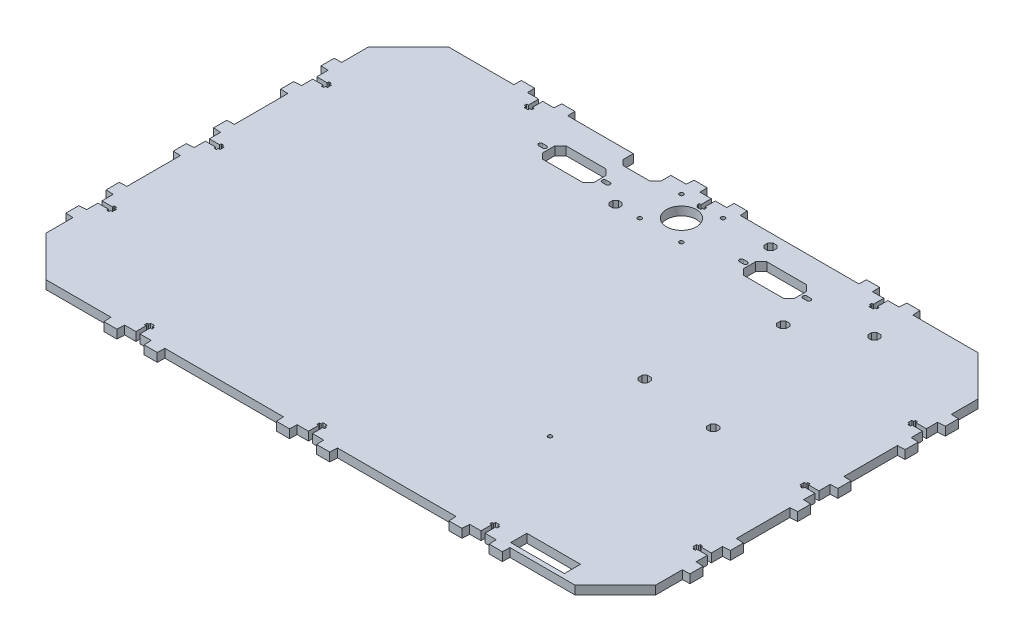
SolidWorks part; units mm, degrees
ref_plane "Front Plane" through (0, 0, 0) normal (0, 0, 1) x (1, 0, 0)
ref_plane "Top Plane" through (0, 0, 0) normal (0, 1, 0) x (1, 0, 0)
ref_plane "Right Plane" through (0, 0, 0) normal (1, 0, 0) x (0, 0, -1)
sketch "Sketch1" plane through (0, 0, 0) normal (0, 1, 0) x (1, 0, 0)
  line L0 (-96.3061, 126.6946) -> (-92.1061, 130.8946)
  line L1 (-92.1061, 130.8946) -> (-62.3561, 130.8946)
  line L2 (-62.3561, 130.8946) -> (-58.1561, 126.6946)
  line L3 (-58.1561, 126.6946) -> (-58.1561, 117.7078)
  line L4 (-58.1561, 117.7078) -> (-62.3561, 113.5078)
  line L5 (-62.3561, 113.5078) -> (-92.1061, 113.5078)
  line L6 (-92.1061, 113.5078) -> (-96.3061, 117.7078)
  line L7 (-96.3061, 117.7078) -> (-96.3061, 126.6946)
  line L8 (-52.1061, 120.7012) -> (-55.1061, 120.7012)
  line L9 (-52.1061, 123.7012) -> (-55.1061, 123.7012)
  line L10 (-102.3561, 123.7012) -> (-99.3561, 123.7012)
  line L11 (-102.3561, 120.7012) -> (-99.3561, 120.7012)
  line L12 (146.0113, 0.3464) -> (148.0322, 2.3673)
  line L13 (143.1576, -145.6002) -> (143.1576, -133.6002)
  line L14 (143.1576, -145.6002) -> (183.1576, -145.6002)
  line L15 (143.1576, -133.6002) -> (183.1576, -133.6002)
  line L16 (188.5789, -149.1002) -> (194.5451, -149.1002)
  line L17 (194.5451, -149.1002) -> (224.5789, -119.0664)
  line L18 (224.5789, -119.0664) -> (224.5789, -99.2238)
  line L19 (224.5789, -99.2238) -> (230.0789, -98.9488)
  line L20 (230.0789, -98.9488) -> (230.0789, -89.2488)
  line L21 (230.0789, -89.2488) -> (224.5789, -88.9738)
  line L22 (224.5789, -88.9738) -> (224.5789, -80.6002)
  line L23 (224.5789, -80.6002) -> (216.8789, -80.6002)
  line L24 (216.8789, -80.6002) -> (216.8789, -81.8488)
  line L25 (216.8789, -81.8488) -> (215.0789, -81.8488)
  line L26 (215.0789, -81.8488) -> (215.0789, -80.6002)
  line L27 (215.0789, -80.6002) -> (213.6789, -80.6002)
  line L28 (213.6789, -80.6002) -> (213.6789, -77.5988)
  line L29 (213.6789, -77.5988) -> (215.0789, -77.5988)
  line L30 (215.0789, -77.5988) -> (215.0789, -76.3488)
  line L31 (215.0789, -76.3488) -> (216.8789, -76.3488)
  line L32 (216.8789, -76.3488) -> (216.8789, -77.5988)
  line L33 (216.8789, -77.5988) -> (224.5789, -77.5988)
  line L34 (224.5789, -77.5988) -> (224.5789, -69.2238)
  line L35 (224.5789, -69.2238) -> (230.0789, -68.9488)
  line L36 (230.0789, -68.9488) -> (230.0789, -59.2488)
  line L37 (230.0789, -59.2488) -> (224.5789, -58.9738)
  line L38 (224.5789, -58.9738) -> (224.5789, -19.1238)
  line L39 (224.5789, -19.1238) -> (230.0789, -18.8488)
  line L40 (230.0789, -18.8488) -> (230.0789, -9.1488)
  line L41 (230.0789, -9.1488) -> (224.5789, -8.8738)
  line L42 (224.5789, -8.8738) -> (224.5789, -0.5002)
  line L43 (224.5789, -0.5002) -> (216.8789, -0.5002)
  line L44 (216.8789, -0.5002) -> (216.8789, -1.7488)
  line L45 (216.8789, -1.7488) -> (215.0789, -1.7488)
  line L46 (215.0789, -1.7488) -> (215.0789, -0.5002)
  line L47 (215.0789, -0.5002) -> (213.6789, -0.5002)
  line L48 (213.6789, -0.5002) -> (213.6789, 2.5012)
  line L49 (213.6789, 2.5012) -> (215.0789, 2.5012)
  line L50 (215.0789, 2.5012) -> (215.0789, 3.7512)
  line L51 (215.0789, 3.7512) -> (216.8789, 3.7512)
  line L52 (216.8789, 3.7512) -> (216.8789, 2.5012)
  line L53 (216.8789, 2.5012) -> (224.5789, 2.5012)
  line L54 (224.5789, 2.5012) -> (224.5789, 10.8762)
  line L55 (224.5789, 10.8762) -> (230.0789, 11.1512)
  line L56 (230.0789, 11.1512) -> (230.0789, 20.8512)
  line L57 (230.0789, 20.8512) -> (224.5789, 21.1262)
  line L58 (224.5789, 21.1262) -> (224.5789, 60.9762)
  line L59 (224.5789, 60.9762) -> (230.0789, 61.2512)
  line L60 (230.0789, 61.2512) -> (230.0789, 70.9512)
  line L61 (230.0789, 70.9512) -> (224.5789, 71.2262)
  line L62 (224.5789, 71.2262) -> (224.5789, 79.5998)
  line L63 (224.5789, 79.5998) -> (216.8789, 79.5998)
  line L64 (216.8789, 79.5998) -> (216.8789, 78.3512)
  line L65 (216.8789, 78.3512) -> (215.0789, 78.3512)
  line L66 (215.0789, 78.3512) -> (215.0789, 79.5998)
  line L67 (215.0789, 79.5998) -> (213.6789, 79.5998)
  line L68 (213.6789, 79.5998) -> (213.6789, 82.6012)
  line L69 (213.6789, 82.6012) -> (215.0789, 82.6012)
  line L70 (215.0789, 82.6012) -> (215.0789, 83.8512)
  line L71 (215.0789, 83.8512) -> (216.8789, 83.8512)
  line L72 (216.8789, 83.8512) -> (216.8789, 82.6012)
  line L73 (216.8789, 82.6012) -> (224.5189, 82.6012)
  line L74 (224.5189, 82.6012) -> (224.5189, 90.9762)
  line L75 (224.5189, 90.9762) -> (230.0189, 91.2512)
  line L76 (230.0189, 91.2512) -> (230.0189, 100.9512)
  line L77 (230.0189, 100.9512) -> (224.5189, 101.2262)
  line L78 (224.5189, 101.2262) -> (224.5189, 121.0674)
  line L79 (224.5189, 121.0674) -> (194.6999, 150.8864)
  line L80 (194.6999, 150.8864) -> (188.5189, 150.8674)
  line L81 (188.5189, 150.8674) -> (146.1439, 150.9012)
  line L82 (146.1439, 150.9012) -> (145.8689, 156.4012)
  line L83 (145.8689, 156.4012) -> (136.1689, 156.4012)
  line L84 (136.1689, 156.4012) -> (135.8939, 150.9012)
  line L85 (135.8939, 150.9012) -> (127.5189, 150.9012)
  line L86 (127.5189, 150.9012) -> (127.5189, 143.2012)
  line L87 (127.5189, 143.2012) -> (128.7689, 143.2012)
  line L88 (128.7689, 143.2012) -> (128.7689, 141.4012)
  line L89 (128.7689, 141.4012) -> (127.5189, 141.4012)
  line L90 (127.5189, 141.4012) -> (127.5189, 140.0012)
  line L91 (127.5189, 140.0012) -> (124.5175, 140.0012)
  line L92 (124.5175, 140.0012) -> (124.5175, 141.4012)
  line L93 (124.5175, 141.4012) -> (123.2689, 141.4012)
  line L94 (123.2689, 141.4012) -> (123.2689, 143.2012)
  line L95 (123.2689, 143.2012) -> (124.5175, 143.2012)
  line L96 (124.5175, 143.2012) -> (124.5175, 150.9012)
  line L97 (124.5175, 150.9012) -> (116.1439, 150.9012)
  line L98 (116.1439, 150.9012) -> (115.8689, 156.4012)
  line L99 (115.8689, 156.4012) -> (106.1689, 156.4012)
  line L100 (106.1689, 156.4012) -> (105.8939, 150.9012)
  line L101 (105.8939, 150.9012) -> (17.6432, 150.9012)
  line L102 (17.6432, 150.9012) -> (17.3682, 156.4012)
  line L103 (17.3682, 156.4012) -> (7.6682, 156.4012)
  line L104 (7.6682, 156.4012) -> (7.3932, 150.9012)
  line L105 (7.3932, 150.9012) -> (-0.9804, 150.9012)
  line L106 (-0.9804, 150.9012) -> (-0.9804, 143.2012)
  line L107 (-0.9804, 143.2012) -> (0.2682, 143.2012)
  line L108 (0.2682, 143.2012) -> (0.2682, 141.4012)
  line L109 (0.2682, 141.4012) -> (-0.9804, 141.4012)
  line L110 (-0.9804, 141.4012) -> (-0.9804, 140.0012)
  line L111 (-0.9804, 140.0012) -> (-3.9818, 140.0012)
  line L112 (-3.9818, 140.0012) -> (-3.9818, 141.4012)
  line L113 (-3.9818, 141.4012) -> (-5.2318, 141.4012)
  line L114 (-5.2318, 141.4012) -> (-5.2318, 143.2012)
  line L115 (-5.2318, 143.2012) -> (-3.9818, 143.2012)
  line L116 (-3.9818, 143.2012) -> (-3.9818, 150.9012)
  line L117 (-3.9818, 150.9012) -> (-12.3568, 150.9012)
  line L118 (-12.3568, 150.9012) -> (-12.6318, 156.4012)
  line L119 (-12.6318, 156.4012) -> (-22.3318, 156.4012)
  line L120 (-22.3318, 156.4012) -> (-22.6068, 150.9012)
  line L121 (-22.6068, 150.9012) -> (-34.055, 150.9012)
  line L122 (-110.8561, 150.9012) -> (-111.1311, 156.4012)
  line L123 (-111.1311, 156.4012) -> (-120.8311, 156.4012)
  line L124 (-120.8311, 156.4012) -> (-121.1061, 150.9012)
  line L125 (-121.1061, 150.9012) -> (-129.4798, 150.9012)
  line L126 (-129.4798, 150.9012) -> (-129.4798, 143.2012)
  line L127 (-129.4798, 143.2012) -> (-128.2311, 143.2012)
  line L128 (-128.2311, 143.2012) -> (-128.2311, 141.4012)
  line L129 (-128.2311, 141.4012) -> (-129.4798, 141.4012)
  line L130 (-129.4798, 141.4012) -> (-129.4798, 140.0012)
  line L131 (-129.4798, 140.0012) -> (-132.4811, 140.0012)
  line L132 (-132.4811, 140.0012) -> (-132.4811, 141.4012)
  line L133 (-132.4811, 141.4012) -> (-133.7311, 141.4012)
  line L134 (-133.7311, 141.4012) -> (-133.7311, 143.2012)
  line L135 (-133.7311, 143.2012) -> (-132.4811, 143.2012)
  line L136 (-132.4811, 143.2012) -> (-132.4811, 150.9012)
  line L137 (-132.4811, 150.9012) -> (-140.8561, 150.9012)
  line L138 (-140.8561, 150.9012) -> (-141.1311, 156.4012)
  line L139 (-141.1311, 156.4012) -> (-150.8311, 156.4012)
  line L140 (-150.8311, 156.4012) -> (-151.1061, 150.9012)
  line L141 (-151.1061, 150.9012) -> (-199.6473, 150.9012)
  line L142 (-199.6473, 150.9012) -> (-229.4811, 121.0674)
  line L143 (-229.4811, 121.0674) -> (-229.4811, 101.2262)
  line L144 (-229.4811, 101.2262) -> (-234.9811, 100.9512)
  line L145 (-234.9811, 100.9512) -> (-234.9811, 91.2512)
  line L146 (-234.9811, 91.2512) -> (-229.4811, 90.9762)
  line L147 (-229.4811, 90.9762) -> (-229.4811, 82.6012)
  line L148 (-229.4811, 82.6012) -> (-221.7811, 82.6012)
  line L149 (-221.7811, 82.6012) -> (-221.7811, 83.8512)
  line L150 (-221.7811, 83.8512) -> (-219.9811, 83.8512)
  line L151 (-219.9811, 83.8512) -> (-219.9811, 82.6012)
  line L152 (-219.9811, 82.6012) -> (-218.5811, 82.6012)
  line L153 (-218.5811, 82.6012) -> (-218.5811, 79.5998)
  line L154 (-218.5811, 79.5998) -> (-219.9811, 79.5998)
  line L155 (-219.9811, 79.5998) -> (-219.9811, 78.3512)
  line L156 (-219.9811, 78.3512) -> (-221.7811, 78.3512)
  line L157 (-221.7811, 78.3512) -> (-221.7811, 79.5998)
  line L158 (-221.7811, 79.5998) -> (-229.4811, 79.5998)
  line L159 (-229.4811, 79.5998) -> (-229.4811, 71.2262)
  line L160 (-229.4811, 71.2262) -> (-234.9811, 70.9512)
  line L161 (-234.9811, 70.9512) -> (-234.9811, 61.2512)
  line L162 (-234.9811, 61.2512) -> (-229.4811, 60.9762)
  line L163 (-229.4811, 60.9762) -> (-229.4811, 21.2262)
  line L164 (-229.4811, 21.2262) -> (-234.9811, 20.9512)
  line L165 (-234.9811, 20.9512) -> (-234.9811, 11.2512)
  line L166 (-234.9811, 11.2512) -> (-229.4811, 10.9762)
  line L167 (-229.4811, 10.9762) -> (-229.4811, 2.6012)
  line L168 (-229.4811, 2.6012) -> (-221.7811, 2.6012)
  line L169 (-221.7811, 2.6012) -> (-221.7811, 3.8512)
  line L170 (-221.7811, 3.8512) -> (-219.9811, 3.8512)
  line L171 (-219.9811, 3.8512) -> (-219.9811, 2.6012)
  line L172 (-219.9811, 2.6012) -> (-218.5811, 2.6012)
  line L173 (-218.5811, 2.6012) -> (-218.5811, -0.4002)
  line L174 (-218.5811, -0.4002) -> (-219.9811, -0.4002)
  line L175 (-219.9811, -0.4002) -> (-219.9811, -1.6488)
  line L176 (-219.9811, -1.6488) -> (-221.7811, -1.6488)
  line L177 (-221.7811, -1.6488) -> (-221.7811, -0.4002)
  line L178 (-221.7811, -0.4002) -> (-229.4811, -0.4002)
  line L179 (-229.4811, -0.4002) -> (-229.4811, -8.7738)
  line L180 (-229.4811, -8.7738) -> (-234.9811, -9.0488)
  line L181 (-234.9811, -9.0488) -> (-234.9811, -18.7488)
  line L182 (-234.9811, -18.7488) -> (-229.4811, -19.0238)
  line L183 (-229.4811, -19.0238) -> (-229.4811, -58.7738)
  line L184 (-229.4811, -58.7738) -> (-234.9811, -59.0488)
  line L185 (-234.9811, -59.0488) -> (-234.9811, -68.7488)
  line L186 (-234.9811, -68.7488) -> (-229.4811, -69.0238)
  line L187 (-229.4811, -69.0238) -> (-229.4811, -77.3988)
  line L188 (-229.4811, -77.3988) -> (-221.7811, -77.3988)
  line L189 (-221.7811, -77.3988) -> (-221.7811, -76.1488)
  line L190 (-221.7811, -76.1488) -> (-219.9811, -76.1488)
  line L191 (-219.9811, -76.1488) -> (-219.9811, -77.3988)
  line L192 (-219.9811, -77.3988) -> (-218.5811, -77.3988)
  line L193 (-218.5811, -77.3988) -> (-218.5811, -80.4002)
  line L194 (-218.5811, -80.4002) -> (-219.9811, -80.4002)
  line L195 (-219.9811, -80.4002) -> (-219.9811, -81.6488)
  line L196 (-219.9811, -81.6488) -> (-221.7811, -81.6488)
  line L197 (-221.7811, -81.6488) -> (-221.7811, -80.4002)
  line L198 (-221.7811, -80.4002) -> (-229.4811, -80.4002)
  line L199 (-229.4811, -80.4002) -> (-229.4811, -88.7738)
  line L200 (-229.4811, -88.7738) -> (-234.9811, -89.0488)
  line L201 (-234.9811, -89.0488) -> (-234.9811, -98.7488)
  line L202 (-234.9811, -98.7488) -> (-229.4811, -99.0238)
  line L203 (-229.4811, -99.0238) -> (-229.4811, -119.0664)
  line L204 (-229.4811, -119.0664) -> (-199.4473, -149.1002)
  line L205 (-199.4473, -149.1002) -> (-151.1061, -149.1002)
  line L206 (-151.1061, -149.1002) -> (-150.8311, -154.6002)
  line L207 (-150.8311, -154.6002) -> (-141.1311, -154.6002)
  line L208 (-141.1311, -154.6002) -> (-140.8561, -149.1002)
  line L209 (-140.8561, -149.1002) -> (-132.4811, -149.1002)
  line L210 (-132.4811, -149.1002) -> (-132.4811, -141.4002)
  line L211 (-132.4811, -141.4002) -> (-133.7311, -141.4002)
  line L212 (-133.7311, -141.4002) -> (-133.7311, -139.6002)
  line L213 (-133.7311, -139.6002) -> (-132.4811, -139.6002)
  line L214 (-132.4811, -139.6002) -> (-132.4811, -138.2002)
  line L215 (-132.4811, -138.2002) -> (-129.4798, -138.2002)
  line L216 (-129.4798, -138.2002) -> (-129.4798, -139.6002)
  line L217 (-129.4798, -139.6002) -> (-128.2311, -139.6002)
  line L218 (-128.2311, -139.6002) -> (-128.2311, -141.4002)
  line L219 (-128.2311, -141.4002) -> (-129.4798, -141.4002)
  line L220 (-129.4798, -141.4002) -> (-129.4798, -149.1002)
  line L221 (-129.4798, -149.1002) -> (-121.1061, -149.1002)
  line L222 (-121.1061, -149.1002) -> (-120.8311, -154.6002)
  line L223 (-120.8311, -154.6002) -> (-111.1311, -154.6002)
  line L224 (-111.1311, -154.6002) -> (-110.8561, -149.1002)
  line L225 (-110.8561, -149.1002) -> (-22.6068, -149.1002)
  line L226 (-22.6068, -149.1002) -> (-22.3318, -154.6002)
  line L227 (-22.3318, -154.6002) -> (-12.6318, -154.6002)
  line L228 (-12.6318, -154.6002) -> (-12.3568, -149.1002)
  line L229 (-12.3568, -149.1002) -> (-3.9818, -149.1002)
  line L230 (-3.9818, -149.1002) -> (-3.9818, -141.4002)
  line L231 (-3.9818, -141.4002) -> (-5.2318, -141.4002)
  line L232 (-5.2318, -141.4002) -> (-5.2318, -139.6002)
  line L233 (-5.2318, -139.6002) -> (-3.9818, -139.6002)
  line L234 (-3.9818, -139.6002) -> (-3.9818, -138.2002)
  line L235 (-3.9818, -138.2002) -> (-0.9804, -138.2002)
  line L236 (-0.9804, -138.2002) -> (-0.9804, -139.6002)
  line L237 (-0.9804, -139.6002) -> (0.2682, -139.6002)
  line L238 (0.2682, -139.6002) -> (0.2682, -141.4002)
  line L239 (0.2682, -141.4002) -> (-0.9804, -141.4002)
  line L240 (-0.9804, -141.4002) -> (-0.9804, -149.1002)
  line L241 (-0.9804, -149.1002) -> (7.3932, -149.1002)
  line L242 (7.3932, -149.1002) -> (7.6682, -154.6002)
  line L243 (7.6682, -154.6002) -> (17.3682, -154.6002)
  line L244 (17.3682, -154.6002) -> (17.6432, -149.1002)
  line L245 (-34.626, 108.2512) -> (-32.605, 110.2722)
  line L246 (105.8939, -149.1002) -> (106.1689, -154.6002)
  line L247 (106.1689, -154.6002) -> (115.8689, -154.6002)
  line L248 (115.8689, -154.6002) -> (116.1439, -149.1002)
  line L249 (116.1439, -149.1002) -> (124.5175, -149.1002)
  line L250 (124.5175, -149.1002) -> (124.5175, -141.4002)
  line L251 (124.5175, -141.4002) -> (123.2689, -141.4002)
  line L252 (123.2689, -141.4002) -> (123.2689, -139.6002)
  line L253 (123.2689, -139.6002) -> (124.5175, -139.6002)
  line L254 (124.5175, -139.6002) -> (124.5175, -138.2002)
  line L255 (124.5175, -138.2002) -> (127.5189, -138.2002)
  line L256 (127.5189, -138.2002) -> (127.5189, -139.6002)
  line L257 (127.5189, -139.6002) -> (128.7689, -139.6002)
  line L258 (128.7689, -139.6002) -> (128.7689, -141.4002)
  line L259 (128.7689, -141.4002) -> (127.5189, -141.4002)
  line L260 (127.5189, -141.4002) -> (127.5189, -149.1002)
  line L261 (127.5189, -149.1002) -> (135.8939, -149.1002)
  line L262 (135.8939, -149.1002) -> (136.1689, -154.6002)
  line L263 (136.1689, -154.6002) -> (145.8689, -154.6002)
  line L264 (145.8689, -154.6002) -> (146.1439, -149.1002)
  line L265 (188.5789, -149.1002) -> (146.1439, -149.1002)
  line L266 (183.1576, -133.6002) -> (183.1576, -145.6002)
  line L267 (-39.505, 110.2722) -> (-37.484, 108.2512)
  line L268 (-37.484, 115.1512) -> (-39.505, 113.1302)
  line L269 (-34.626, 115.1512) -> (-37.484, 115.1512)
  line L270 (-37.484, 108.2512) -> (-34.626, 108.2512)
  line L271 (-39.505, 113.1302) -> (-39.505, 110.2722)
  line L272 (-32.605, 113.1302) -> (-34.626, 115.1512)
  line L273 (17.6432, -149.1002) -> (105.8939, -149.1002)
  line L274 (-2.4811, 140.0012) -> (-2.4811, 116.0719) construction
  line L275 (97.3939, 120.7012) -> (94.3939, 120.7012)
  line L276 (97.3939, 123.7012) -> (94.3939, 123.7012)
  line L277 (47.1439, 123.7012) -> (50.1439, 123.7012)
  line L278 (47.1439, 120.7012) -> (50.1439, 120.7012)
  line L279 (91.3439, 117.7078) -> (91.3439, 126.6946)
  line L280 (87.1439, 113.5078) -> (91.3439, 117.7078)
  line L281 (57.3939, 113.5078) -> (87.1439, 113.5078)
  line L282 (53.1939, 117.7078) -> (57.3939, 113.5078)
  line L283 (53.1939, 126.6946) -> (53.1939, 117.7078)
  line L284 (57.3939, 130.8946) -> (53.1939, 126.6946)
  line L285 (87.1439, 130.8946) -> (57.3939, 130.8946)
  line L286 (91.3439, 126.6946) -> (87.1439, 130.8946)
  line L287 (-77.2311, 113.5078) -> (-77.2311, 130.8946) construction
  line L288 (141.1322, 2.3673) -> (143.1532, 0.3464)
  line L289 (-32.605, 110.2722) -> (-32.605, 113.1302)
  line L290 (143.1532, 7.2464) -> (141.1322, 5.2254)
  line L291 (146.0113, 7.2464) -> (143.1532, 7.2464)
  line L292 (143.1532, 0.3464) -> (146.0113, 0.3464)
  line L293 (141.1322, 5.2254) -> (141.1322, 2.3673)
  line L294 (145.5822, 122.7964) -> (104.2222, 96.2964) construction
  line L295 (104.2222, 96.2964) -> (144.5822, 3.7964) construction
  line L296 (144.5822, 3.7964) -> (87.5822, 9.7964) construction
  line L297 (87.5822, 9.7964) -> (49.1672, 141.8464) construction
  line L298 (49.1672, 141.8464) -> (145.5822, 122.7964) construction
  line L299 (194.6999, 150.8864) -> (224.5189, 150.8864) construction
  line L300 (224.5189, 150.8864) -> (89.2289, -62.4036) construction
  line L301 (-62.055, 150.9012) -> (-110.8561, 150.9012)
  line L302 (-62.055, 150.9012) -> (-34.055, 150.9012) construction
  line L303 (-34.055, 150.9012) -> (-34.055, 143.4012)
  line L304 (-38.055, 139.4012) -> (-58.055, 139.4012)
  line L305 (-62.055, 150.9012) -> (-62.055, 143.4012)
  line L306 (-48.055, 150.9012) -> (-48.055, 139.4012) construction
  line L307 (-62.055, 143.4012) -> (-58.055, 139.4012)
  line L308 (-34.055, 143.4012) -> (-38.055, 139.4012)
  line L309 (148.0322, 5.2254) -> (146.0113, 7.2464)
  line L310 (148.0322, 2.3673) -> (148.0322, 5.2254)
  line L311 (89.0113, 6.3464) -> (91.0322, 8.3673)
  line L312 (84.1322, 8.3673) -> (86.1532, 6.3464)
  line L313 (86.1532, 13.2464) -> (84.1322, 11.2254)
  line L314 (89.0113, 13.2464) -> (86.1532, 13.2464)
  line L315 (86.1532, 6.3464) -> (89.0113, 6.3464)
  line L316 (84.1322, 11.2254) -> (84.1322, 8.3673)
  line L317 (91.0322, 11.2254) -> (89.0113, 13.2464)
  line L318 (91.0322, 8.3673) -> (91.0322, 11.2254)
  line L319 (50.5963, 138.3964) -> (52.6172, 140.4173)
  line L320 (45.7172, 140.4173) -> (47.7382, 138.3964)
  line L321 (47.7382, 145.2964) -> (45.7172, 143.2754)
  line L322 (50.5963, 145.2964) -> (47.7382, 145.2964)
  line L323 (47.7382, 138.3964) -> (50.5963, 138.3964)
  line L324 (45.7172, 143.2754) -> (45.7172, 140.4173)
  line L325 (52.6172, 143.2754) -> (50.5963, 145.2964)
  line L326 (52.6172, 140.4173) -> (52.6172, 143.2754)
  line L327 (105.6513, 92.8464) -> (107.6722, 94.8673)
  line L328 (100.7722, 94.8673) -> (102.7932, 92.8464)
  line L329 (102.7932, 99.7464) -> (100.7722, 97.7254)
  line L330 (105.6513, 99.7464) -> (102.7932, 99.7464)
  line L331 (102.7932, 92.8464) -> (105.6513, 92.8464)
  line L332 (100.7722, 97.7254) -> (100.7722, 94.8673)
  line L333 (107.6722, 97.7254) -> (105.6513, 99.7464)
  line L334 (107.6722, 94.8673) -> (107.6722, 97.7254)
  line L335 (147.0113, 119.3464) -> (149.0322, 121.3673)
  line L336 (142.1322, 121.3673) -> (144.1532, 119.3464)
  line L337 (144.1532, 126.2464) -> (142.1322, 124.2254)
  line L338 (147.0113, 126.2464) -> (144.1532, 126.2464)
  line L339 (144.1532, 119.3464) -> (147.0113, 119.3464)
  line L340 (142.1322, 124.2254) -> (142.1322, 121.3673)
  line L341 (149.0322, 124.2254) -> (147.0113, 126.2464)
  line L342 (149.0322, 121.3673) -> (149.0322, 124.2254)
  arc A0 (-52.1061, 123.7012) -> (-52.1061, 120.7012) centre (-52.1061, 122.2012) cw
  arc A1 (-55.1061, 120.7012) -> (-55.1061, 123.7012) centre (-55.1061, 122.2012) cw
  arc A2 (-99.3561, 120.7012) -> (-99.3561, 123.7012) centre (-99.3561, 122.2012) ccw
  arc A3 (-102.3561, 123.7012) -> (-102.3561, 120.7012) centre (-102.3561, 122.2012) ccw
  circle A4 centre (-36.055, 111.7012) radius 3.45 construction
  arc A5 (97.3939, 123.7012) -> (97.3939, 120.7012) centre (97.3939, 122.2012) cw
  circle A6 centre (-2.4811, 127.1969) radius 11.125
  arc A7 (94.3939, 120.7012) -> (94.3939, 123.7012) centre (94.3939, 122.2012) cw
  arc A8 (50.1439, 120.7012) -> (50.1439, 123.7012) centre (50.1439, 122.2012) ccw
  circle A9 centre (89.2289, -62.4036) radius 1.5
  circle A10 centre (144.5822, 3.7964) radius 3.45 construction
  circle A11 centre (87.5822, 9.7964) radius 3.45 construction
  circle A12 centre (49.1672, 141.8464) radius 3.45 construction
  circle A13 centre (104.2222, 96.2964) radius 3.45 construction
  circle A14 centre (145.5822, 122.7964) radius 3.45 construction
  circle A20 centre (-17.9811, 142.7012) radius 1.5
  arc A30 (47.1439, 123.7012) -> (47.1439, 120.7012) centre (47.1439, 122.2012) ccw
  circle A63 centre (13.0189, 111.7012) radius 1.5
  circle A117 centre (-17.9811, 111.7012) radius 1.5
  circle A118 centre (13.0189, 142.7012) radius 1.5
  dimension "D1" = 22.25
  dimension "D2" = 3.5
  dimension "D3" = 12
  dimension "D6" = 213.29
  dimension "D7" = 135.29
  dimension "D8" = 3
extrude "Boss-Extrude1" add sketch "Sketch1" along normal blind 6.4
